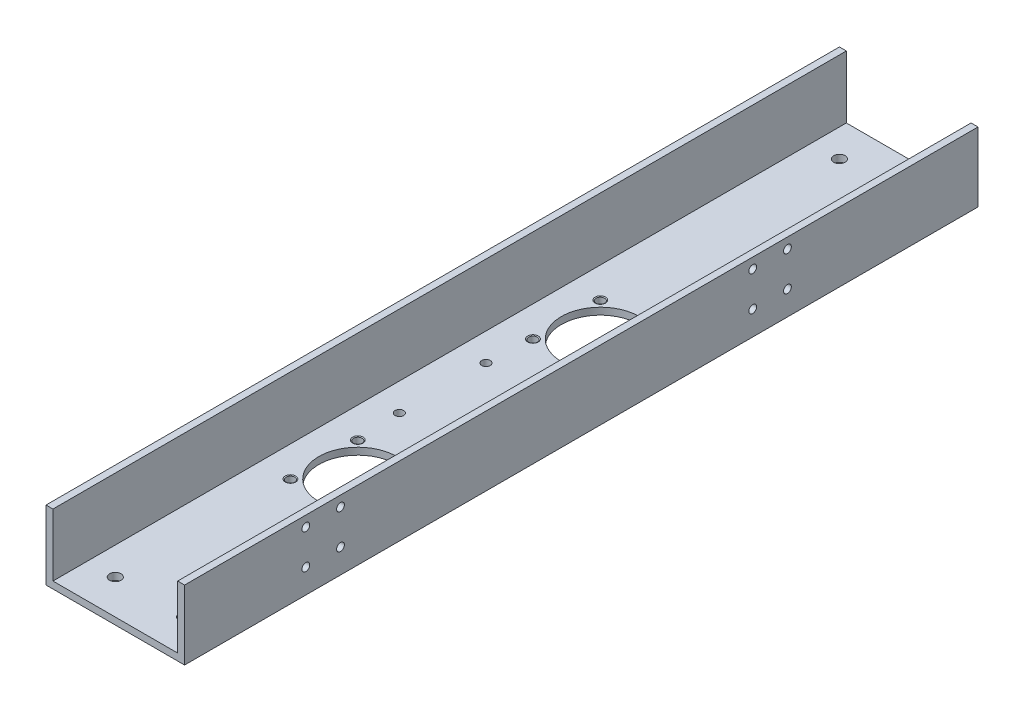
SolidWorks part; units mm, degrees
material "Д16Т ГОСТ 4784-74"
ref_plane "Спереди" through (0, 0, 0) normal (0, 0, 1) x (1, 0, 0)
ref_plane "Сверху" through (0, 0, 0) normal (0, 1, 0) x (1, 0, 0)
ref_plane "Справа" through (0, 0, 0) normal (1, 0, 0) x (0, 0, -1)
sketch "Эскиз1" plane through (0, 0, 0) normal (0, 0, 1) x (1, 0, 0)
  line L0 (0, 0) -> (0, 40)
  line L1 (0, 40) -> (4, 40)
  line L2 (4, 40) -> (4, 4)
  line L3 (4, 4) -> (76, 4)
  line L4 (76, 4) -> (76, 40)
  line L5 (76, 40) -> (80, 40)
  line L6 (80, 40) -> (80, 0)
  line L7 (80, 0) -> (0, 0)
  line L8 (4, 4) -> (4, 0) construction
  dimension "D1" = 4
  dimension "D2" = 40
  dimension "D3" = 80
extrude "Бобышка-Вытянуть1" add sketch "Эскиз1" along normal blind 298
sketch "Эскиз2" plane through (0, 0, 0) normal (0, -1, 0) x (1, 0, 0)
  line L0 (80, 149) -> (0, 149) construction
  line L1 (80, 298) -> (80, 0) construction
  line L2 (0, 298) -> (0, 0) construction
  line L3 (0, 298) -> (80, 298) construction
  circle A0 centre (41, 219) radius 22.5
  circle A1 centre (41, 79) radius 22.5
  dimension "D1" = 41
  dimension "D2" = 79
  dimension "D3" = 45
extrude "Вырез-Вытянуть1" cut sketch "Эскиз2" against normal through all
hole_wizard "Отверстие обработанное метчиком M62" positions "Эскиз6" profile "Эскиз5" tap size "M6" standard "DIN"
sketch "Эскиз6" plane through (0, 4, 0) normal (0, 1, 0) x (-1, 0, 0)
  line L0 (-80, 149) -> (0, 149) construction
  line L1 (-80, 298) -> (-80, 0) construction
  line L2 (0, 298) -> (0, 0) construction
  line L5 (-21.5546, 59.5546) -> (-60.4454, 59.5546)
  line L6 (-21.5546, 59.5546) -> (-21.5546, 98.4454)
  line L7 (-21.5546, 98.4454) -> (-60.4454, 98.4454)
  line L8 (-60.4454, 59.5546) -> (-60.4454, 98.4454)
  line L9 (-60.4454, 238.4454) -> (-60.4454, 199.5546)
  line L10 (-21.5546, 199.5546) -> (-60.4454, 199.5546)
  line L11 (-21.5546, 238.4454) -> (-21.5546, 199.5546)
  line L12 (-21.5546, 238.4454) -> (-60.4454, 238.4454)
  circle A0 centre (-41, 79) radius 27.5
  circle A1 centre (-41, 219) radius 27.5
  point P0 (-21.5546, 98.4454)
  point P66 (-21.5546, 59.5546)
  point P68 (-60.4454, 59.5546)
  point P70 (-60.4454, 98.4454)
  point P79 (-60.4454, 199.5546)
  point P80 (-60.4454, 238.4454)
  point P81 (-21.5546, 238.4454)
  point P82 (-21.5546, 199.5546)
  dimension "D1" = 55
sketch "Эскиз5" plane through (21.5546, 4, 98.4454) normal (1, 0, 0) x (0, 0, 1)
  line L0 (0, 0) -> (0, 18.5022)
  line L1 (0, 18.5022) -> (2.5, 17)
  line L2 (2.5, 17) -> (2.5, 0.3031)
  line L3 (2.5, 0.3031) -> (3.025, 0)
  line L5 (3.025, 0) -> (0, 0)
  line L6 (-2.5, 0.3031) -> (-3.025, 0) construction
  line L10 (0, 18.5022) -> (-2.5, 17) construction
  line L11 (0, -6.35) -> (0, 107.95) construction
  dimension "Диаметр сверла" = 5
  dimension "Глубина сверла" = 17
  dimension "Диаметр передней зенковки" = 6.05
  dimension "Угол передней зенковки" = 120
  dimension "Угол заточки сверла" = 118
cosmetic thread "Отверстие резьбы5" parameters "D1"=4, "D2"=6
cosmetic thread "Отверстие резьбы6" parameters "D1"=4, "D2"=6
cosmetic thread "Отверстие резьбы7" parameters "D1"=4, "D2"=6
cosmetic thread "Отверстие резьбы8" parameters "D1"=4, "D2"=6
cosmetic thread "Отверстие резьбы9" parameters "D1"=4, "D2"=6
cosmetic thread "Отверстие резьбы10" parameters "D1"=4, "D2"=6
cosmetic thread "Отверстие резьбы11" parameters "D1"=4, "D2"=6
cosmetic thread "Отверстие резьбы12" parameters "D1"=4, "D2"=6
hole_wizard "Отверстие с зазором M42" positions "Эскиз10" profile "Эскиз9" hole size "M4" standard "DIN"
sketch "Эскиз10" plane through (80, 0, 0) normal (1, 0, 0) x (0, 0, -1)
  line L0 (-298, 0) -> (-298, 40) construction
  line L1 (-298, 40) -> (0, 40) construction
  line L2 (0, 0) -> (0, 40) construction
  point P0 (-288, 34)
  point P1 (-30, 34)
  point P17 (-268, 34)
  point P18 (-10, 34)
  point P19 (-288, 14)
  point P20 (-30, 14)
  point P21 (-268, 14)
  point P22 (-10, 14)
  dimension "D1" = 10
  dimension "D2" = 6
  dimension "D3" = 30
  dimension "D4" = 2
  dimension "D5" = 2
sketch "Эскиз9" plane through (80, 34, 288) normal (0, 1, 0) x (0, 0, -1)
  line L0 (0, 0) -> (0, 6.3519)
  line L1 (0, 6.3519) -> (2.25, 5)
  line L2 (2.25, 5) -> (2.25, 0)
  line L5 (2.25, 0) -> (0, 0)
  line L10 (0, 6.3519) -> (-2.25, 5) construction
  line L11 (0, -6.35) -> (0, 107.95) construction
  dimension "Диаметр отверстия" = 4.5
  dimension "Глубина отверстия" = 5
  dimension "Угол заточки сверла" = 118
hole_wizard "Отверстие обработанное метчиком M63" positions "Эскиз14" profile "Эскиз13" tap size "M6" standard "DIN"
sketch "Эскиз14" plane through (0, 0, 0) normal (0, -1, 0) x (1, 0, 0)
  line L1 (20, 124) -> (60, 124)
  line L2 (20, 124) -> (20, 174)
  line L3 (20, 174) -> (60, 174)
  line L4 (60, 124) -> (60, 174)
  line L5 (0, 149) -> (20, 149)
  line L6 (0, 298) -> (0, 0) construction
  line L8 (60, 149) -> (80, 149)
  line L9 (80, 298) -> (80, 0) construction
  point P0 (20, 124)
  point P1 (20, 174)
  point P3 (60, 174)
  point P5 (60, 124)
  dimension "D1" = 20
  dimension "D2" = 50
sketch "Эскиз13" plane through (20, 0, 124) normal (1, 0, 0) x (0, 0, -1)
  line L0 (0, 0) -> (0, 18.5022)
  line L1 (0, 18.5022) -> (2.5, 17)
  line L2 (2.5, 17) -> (2.5, 0.3031)
  line L3 (2.5, 0.3031) -> (3.025, 0)
  line L5 (3.025, 0) -> (0, 0)
  line L6 (-2.5, 0.3031) -> (-3.025, 0) construction
  line L10 (0, 18.5022) -> (-2.5, 17) construction
  line L11 (0, -6.35) -> (0, 107.95) construction
  dimension "Диаметр сверла" = 5
  dimension "Глубина сверла" = 17
  dimension "Диаметр передней зенковки" = 6.05
  dimension "Угол передней зенковки" = 120
  dimension "Угол заточки сверла" = 118
cosmetic thread "Отверстие резьбы13" parameters "D1"=4, "D2"=6
cosmetic thread "Отверстие резьбы14" parameters "D1"=4, "D2"=6
cosmetic thread "Отверстие резьбы15" parameters "D1"=4, "D2"=6
cosmetic thread "Отверстие резьбы16" parameters "D1"=4, "D2"=6
sketch "Эскиз15" plane through (0, 0, 298) normal (0, 0, 1) x (1, 0, 0)
  line L0 (4, 4) -> (4, 40)
  line L1 (4, 4) -> (4, 40)
  line L2 (4, 40) -> (0, 40)
  line L3 (4, 40) -> (0, 40)
  line L4 (0, 40) -> (0, 0)
  line L5 (0, 40) -> (0, 0)
  line L6 (0, 0) -> (80, 0)
  line L7 (0, 0) -> (80, 0)
  line L8 (80, 0) -> (80, 40)
  line L9 (80, 0) -> (80, 40)
  line L10 (76, 40) -> (76, 4)
  line L11 (76, 40) -> (76, 4)
  line L12 (80, 40) -> (76, 40)
  line L13 (80, 40) -> (76, 40)
  line L14 (76, 4) -> (4, 4)
extrude "Бобышка-Вытянуть2" add sketch "Эскиз15" along normal blind 60
sketch "Эскиз17" plane through (0, 0, 0) normal (0, 0, -1) x (-1, 0, 0)
  line L0 (-4, 4) -> (-4, 40)
  line L1 (-4, 4) -> (-4, 40)
  line L2 (-76, 4) -> (-4, 4)
  line L3 (-76, 4) -> (-4, 4)
  line L4 (-76, 40) -> (-76, 4)
  line L5 (-76, 40) -> (-76, 4)
  line L6 (-80, 40) -> (-76, 40)
  line L7 (-80, 40) -> (-76, 40)
  line L8 (-80, 0) -> (-80, 40)
  line L9 (-80, 0) -> (-80, 40)
  line L10 (0, 0) -> (-80, 0)
  line L11 (0, 0) -> (-80, 0)
  line L12 (0, 40) -> (0, 0)
  line L13 (0, 40) -> (0, 0)
  line L14 (-4, 40) -> (0, 40)
  line L15 (-4, 40) -> (0, 40)
extrude "Бобышка-Вытянуть3" add sketch "Эскиз17" along normal blind 100
hole_wizard "Отверстие с зазором M61" positions "Эскиз12" profile "Эскиз11" hole size "M6" standard "DIN"
sketch "Эскиз12" plane through (0, 4, 0) normal (0, 1, 0) x (-1, 0, 0)
  line L0 (-4, 358) -> (-4, -100) construction
  line L2 (0, 129) -> (-80, 129) construction
  line L3 (0, 358) -> (0, -100) construction
  line L4 (-80, 358) -> (-80, -100) construction
  line L5 (-76, 358) -> (-4, 358) construction
  point P0 (-20, 338)
  point P1 (-60, 338)
  point P17 (-60, -80)
  point P18 (-20, -80)
  dimension "D1" = 16
  dimension "D2" = 40
  dimension "D3" = 20
sketch "Эскиз11" plane through (20, 4, 338) normal (1, 0, 0) x (0, 0, 1)
  line L0 (0, 0) -> (0, 6.9828)
  line L1 (0, 6.9828) -> (3.3, 5)
  line L2 (3.3, 5) -> (3.3, 0)
  line L5 (3.3, 0) -> (0, 0)
  line L10 (0, 6.9828) -> (-3.3, 5) construction
  line L11 (0, -6.35) -> (0, 107.95) construction
  dimension "Диаметр отверстия" = 6.6
  dimension "Глубина отверстия" = 5
  dimension "Угол заточки сверла" = 118
